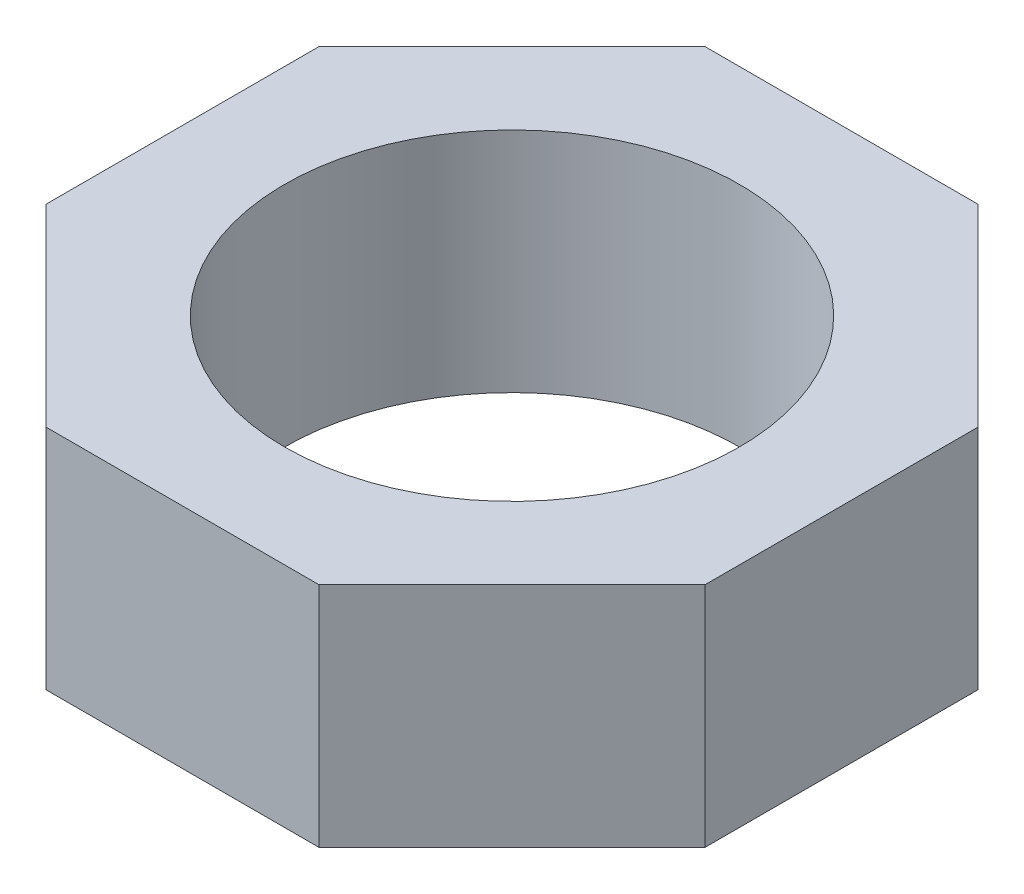
SolidWorks part; units mm, degrees
material "AISI 1020"
ref_plane "Plano frontal" through (0, 0, 0) normal (0, 0, 1) x (1, 0, 0)
ref_plane "Plano superior" through (0, 0, 0) normal (0, 1, 0) x (1, 0, 0)
ref_plane "Plano direito" through (0, 0, 0) normal (1, 0, 0) x (0, 0, -1)
sketch "Esboço1" plane through (0, 0, 0) normal (0, 1, 0) x (1, 0, 0)
  line L0 (-3, 7.2426) -> (3, 7.2426)
  line L1 (3, 7.2426) -> (7.2426, 3)
  line L2 (7.2426, 3) -> (7.2426, -3)
  line L3 (7.2426, -3) -> (3, -7.2426)
  line L4 (3, -7.2426) -> (-3, -7.2426)
  line L5 (-3, -7.2426) -> (-7.2426, -3)
  line L6 (-7.2426, -3) -> (-7.2426, 3)
  line L7 (-7.2426, 3) -> (-3, 7.2426)
  circle A0 centre (0, 0) radius 5
  point P5 (0, 7.2426)
  point P12 (7.2426, 0)
  dimension "D1" = 10
  dimension "D2" = 6
  dimension "D3" = 135
extrude "Ressalto-extrusão1" add sketch "Esboço1" along normal blind 5
